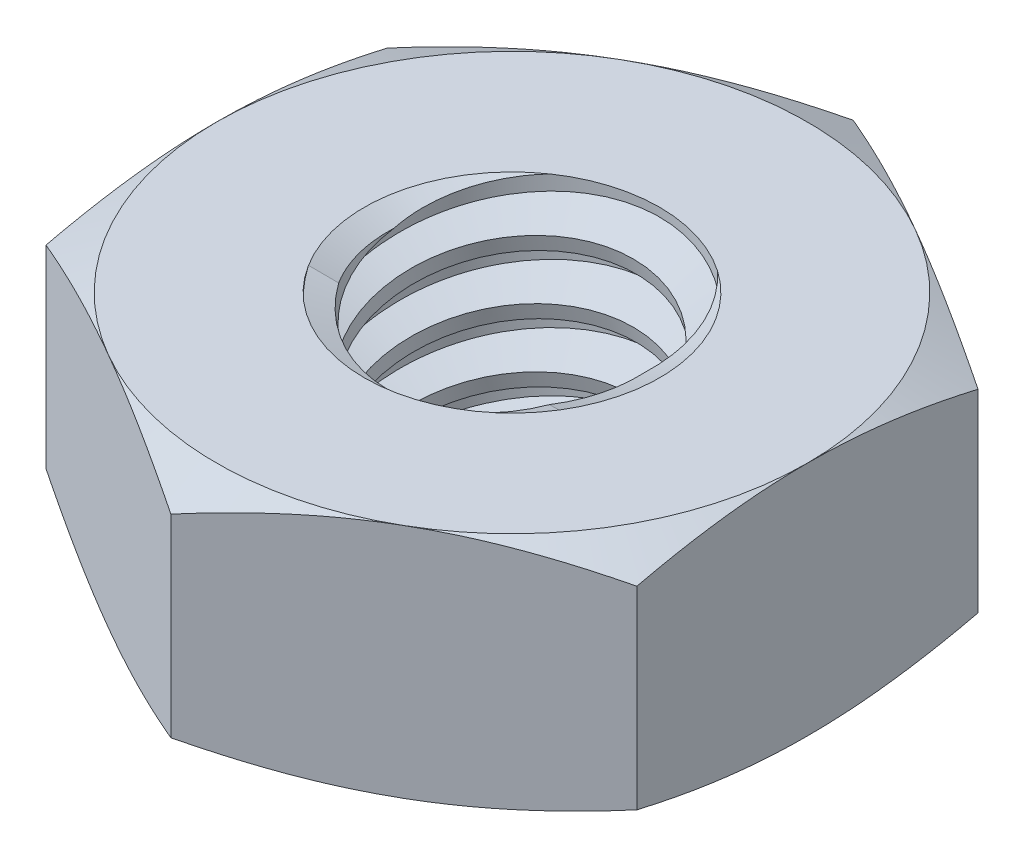
SolidWorks part; units mm, degrees
ref_plane "Front" through (0, 0, 0) normal (0, 0, 1) x (1, 0, 0)
ref_plane "Top" through (0, 0, 0) normal (0, 1, 0) x (1, 0, 0)
ref_plane "Right" through (0, 0, 0) normal (1, 0, 0) x (0, 0, -1)
sketch "Sketch1" plane through (0, 0, 0) normal (0, 1, 0) x (1, 0, 0)
  line L1 (0, 2.3094) -> (-2, 1.1547)
  line L2 (-2, 1.1547) -> (-2, -1.1547)
  line L3 (-2, -1.1547) -> (0, -2.3094)
  line L4 (0, -2.3094) -> (2, -1.1547)
  line L5 (2, -1.1547) -> (2, 1.1547)
  line L6 (2, 1.1547) -> (0, 2.3094)
  circle A0 centre (0, 0) radius 2 construction
  dimension "Hex Flats" = 4
extrude "Extrude1" add sketch "Sketch1" along normal mid plane 1.6
sketch "Sketch2" plane through (0, 0, 0) normal (1, 0, 0) x (0, 0, -1)
  line L0 (-1, -0.8) -> (-1, 0.8) construction
  line L1 (0, -0.8) -> (1, -0.8)
  line L2 (0, -0.8) -> (0, 0.8)
  line L3 (0, 0.8) -> (1, 0.8)
  line L4 (1, -0.8) -> (1, 0.8)
  line L5 (-1.1547, 0.8) -> (1.1547, 0.8) construction
  line L6 (-1.1547, -0.8) -> (1.1547, -0.8) construction
  line L7 (0, -1.8) -> (0, -0.8) construction
  dimension "Thread Dia" = 2
revolve "Revolve1" add sketch "Sketch2" angle 360 about L7
sketch "Sketch3" plane through (0, 0, 0) normal (1, 0, 0) x (0, 0, -1)
  line L0 (1, 0.8) -> (-1, 0.8) construction
  line L1 (-1, 0.8) -> (-1, 0.4) construction
  line L2 (-1, 0.4) -> (1, 0.8) construction
  line L3 (1, 0.8) -> (1.0098, 0.751) construction
  line L4 (1.0098, 0.751) -> (1.0784, 0.4078)
  line L5 (1.0784, 0.4078) -> (0.8416, 0.4879)
  line L6 (0.8416, 0.4879) -> (0.822, 0.5859)
  line L7 (0.822, 0.5859) -> (1.0098, 0.751)
  line L8 (0.8318, 0.5369) -> (1.0441, 0.5794) construction
  line L9 (1, 0.8) -> (1, 0.5705) construction
  line L10 (1, 0.5705) -> (-1, 0.1705) construction
  line L11 (-1, 0.1705) -> (-1, 0.4) construction
  line L12 (-0.0859, 0.8) -> (0.0859, -0.0589) construction
  line L13 (-1, -0.8) -> (-1, 0.8) construction
  line L14 (0, 0.8) -> (1, 0.8) construction
  line L15 (1, -0.8) -> (1, 0.8) construction
  line L16 (0, 0) -> (0, 0.8) construction
  line L17 (-1.0098, 0.751) -> (-1.0784, 0.4078) construction
  line L18 (-0.822, 0.5859) -> (-1.0098, 0.751) construction
  line L19 (-0.8416, 0.4879) -> (-0.822, 0.5859) construction
  line L20 (-1.0784, 0.4078) -> (-0.8416, 0.4879) construction
  line L21 (0.0859, 0.8) -> (-0.0859, -0.0589) construction
  point P13 (0, 0.3705)
  dimension "D1" = 0.05
  dimension "D2" = 0.1
  dimension "Thread Pitch" = 0.4
  dimension "D4" = 60
  dimension "D5" = 0.4
revolve "Cut-Revolve1" cut sketch "Sketch3" angle 360 about L12
pattern_linear "LPattern1" count 4 spacing 0.4 along (0, -1, 0) count 2 spacing 0.4 along (0, 1, 0) of "Cut-Revolve1"
sketch "Sketch4" plane through (0, 0, 0) normal (1, 0, 0) x (0, 0, -1)
  line L0 (0, 0.8) -> (1, 0.8)
  line L1 (1, 0.8) -> (0.822, 0.717)
  line L2 (0.822, 0.717) -> (0.822, -0.717)
  line L3 (0.822, -0.717) -> (1, -0.8)
  line L4 (1, -0.8) -> (0, -0.8)
  line L5 (0, -0.8) -> (0, 0.8)
  line L6 (1, -0.8) -> (1, 0.8) construction
  line L7 (0, 0.8) -> (1, 0.8) construction
  line L8 (0, -0.8) -> (1, -0.8) construction
  line L9 (0, -0.8) -> (0, 0.8) construction
  line L10 (0, 0.8) -> (0, 0.9964) construction
  dimension "D1" = 25
revolve "Cut-Revolve2" cut sketch "Sketch4" angle 360 about L10
combine bodies "Combine1" operation type subtract main body 112 bodies to subtract 111
sketch "Sketch5" plane through (0, 0, 0) normal (1, 0, 0) x (0, 0, -1)
  line L0 (0, -0.8) -> (2, -0.8)
  line L1 (2, -0.8) -> (2.3094, -0.6557)
  line L2 (2.3094, -0.6557) -> (2.3094, 0.6557)
  line L3 (2.3094, 0.6557) -> (2, 0.8)
  line L4 (0, 0.8) -> (0, 2.07)
  line L5 (0, 2.07) -> (3.5794, 2.07)
  line L6 (3.5794, 2.07) -> (3.5794, -2.07)
  line L7 (3.5794, -2.07) -> (0, -2.07)
  line L8 (0, -2.07) -> (0, -0.8)
  line L9 (2, 0.8) -> (2, -0.8) construction
  line L11 (0, -0.8) -> (1, -0.8) construction
  line L12 (2, 0.8) -> (0, 0.8)
  line L13 (2.3094, 0) -> (3.5794, 0) construction
  line L14 (2.3094, 0.8) -> (2.3094, -0.8) construction
  line L15 (0, -0.8) -> (0, 0.8) construction
  line L17 (0, 0) -> (2, 0) construction
  line L22 (0, 0.8) -> (1, 0.8) construction
  dimension "D1" = 25
  dimension "D2" = 1.27
  dimension "D3" = 1.6
revolve "Cut-Revolve3" cut sketch "Sketch5" angle 360 about L15
equation "\"D1@Sketch3\"=\"Thread Pitch@Sketch3\"/8"
equation "\"D2@Sketch3\"=\"Thread Pitch@Sketch3\"/4"
equation "\"D5@Sketch3\"=\"Thread Pitch@Sketch3\""
equation "\"D4@LPattern1\"=\"Thread Pitch@Sketch3\""
equation "\"D3@LPattern1\"=\"Thread Pitch@Sketch3\""
equation "\"D1@LPattern1\"=\"Height@Extrude1\"/\"Thread Pitch@Sketch3\""
